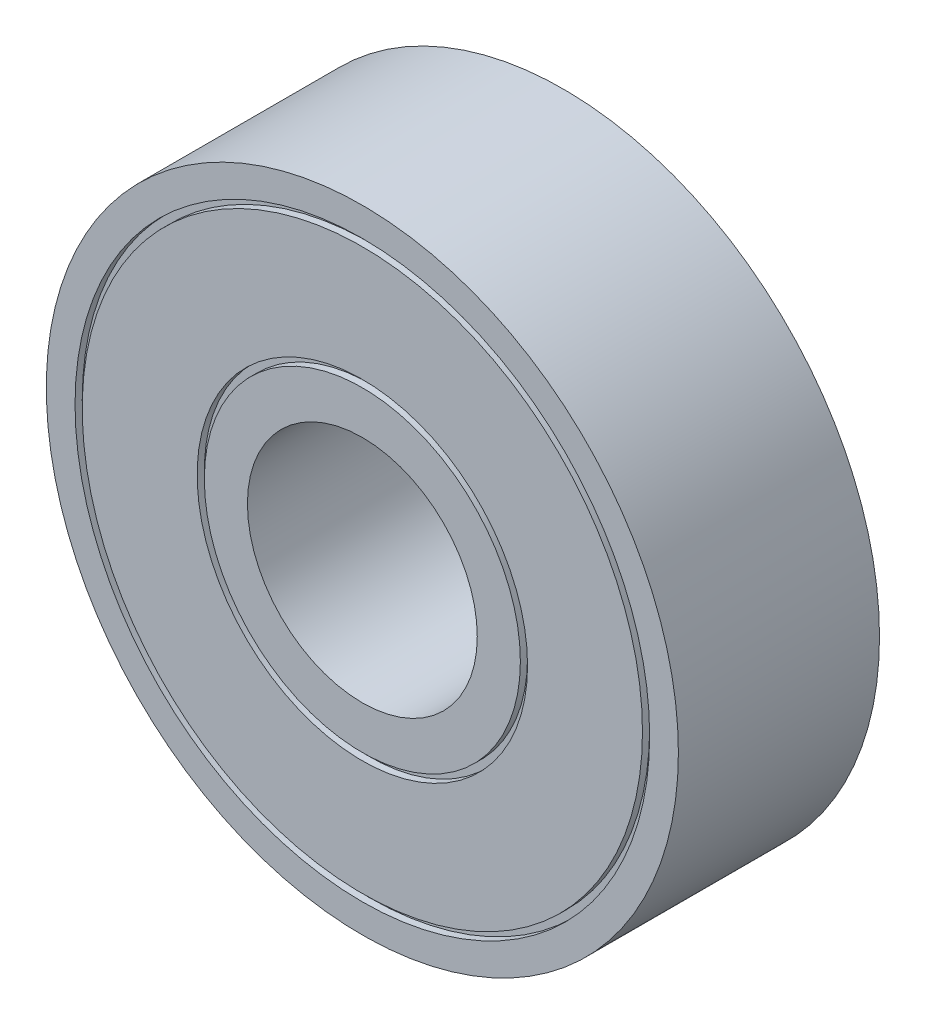
SolidWorks part; units mm, degrees
material "ASTM A36 Aço"
ref_plane "Plano frontal" through (0, 0, 0) normal (0, 0, 1) x (1, 0, 0)
ref_plane "Plano superior" through (0, 0, 0) normal (0, 1, 0) x (1, 0, 0)
ref_plane "Plano direito" through (0, 0, 0) normal (1, 0, 0) x (0, 0, -1)
sketch "Esboço1" plane through (0, 0, 0) normal (0, 0, 1) x (1, 0, 0)
  circle A0 centre (0, 0) radius 4
  circle A1 centre (0, 0) radius 11
  dimension "D1" = 8
  dimension "D2" = 22
extrude "Ressalto-extrusão1" add sketch "Esboço1" along normal mid plane 7
sketch "Esboço2" plane through (0, 0, 3.5) normal (0, 0, 1) x (1, 0, 0)
  circle A0 centre (0, 0) radius 10
  circle A1 centre (0, 0) radius 11
  circle A2 centre (0, 0) radius 11
  circle A3 centre (0, 0) radius 9.75
  circle A4 centre (0, 0) radius 5.75
  circle A5 centre (0, 0) radius 5.5
  circle A6 centre (0, 0) radius 5.5
  dimension "D1" = 0
  dimension "D2" = 1.5
  dimension "D3" = 0.25
  dimension "D4" = 1
  dimension "D5" = 0.25
extrude "Corte-extrusão1" cut sketch "Esboço2" against normal blind 0.25 contours A4 A6 | A0 A3
mirror "Espelhar1" about plane through (0, 0, 0) normal (0, 0, 1) of "Corte-extrusão1"
